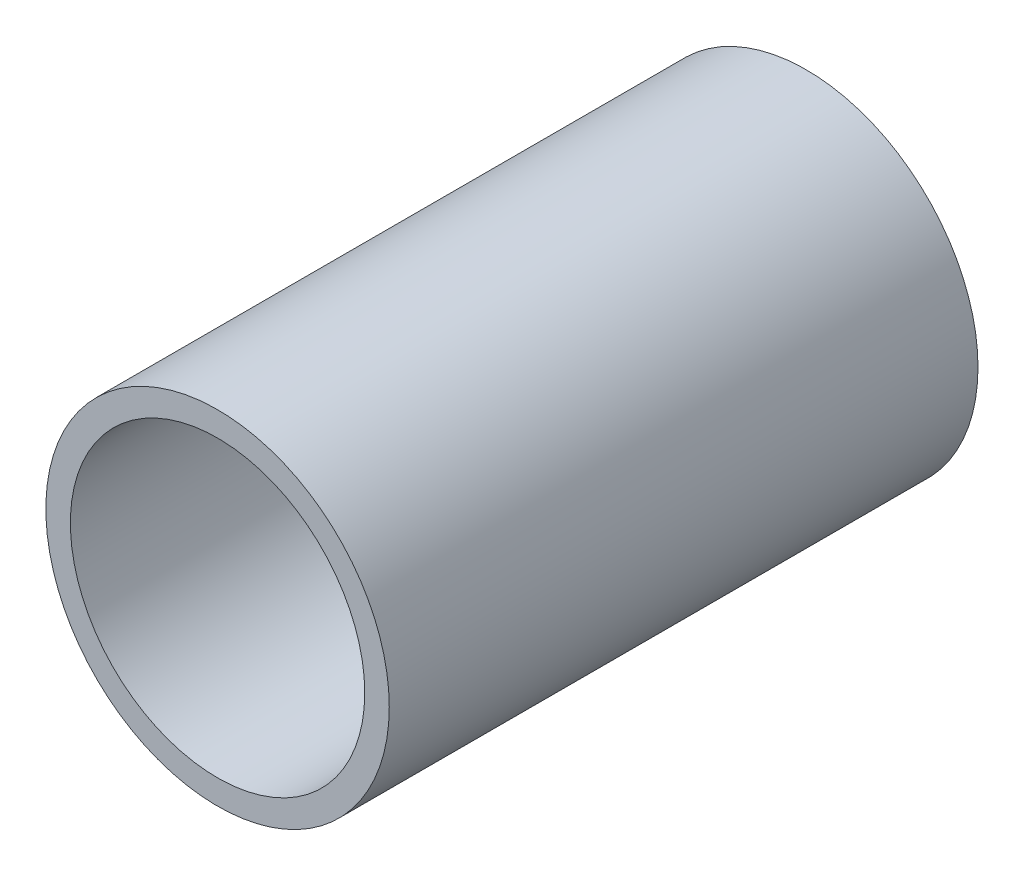
SolidWorks part; units mm, degrees
ref_plane "Alzado" through (0, 0, 0) normal (0, 0, 1) x (1, 0, 0)
ref_plane "Planta" through (0, 0, 0) normal (0, 1, 0) x (1, 0, 0)
ref_plane "Vista lateral" through (0, 0, 0) normal (1, 0, 0) x (0, 0, -1)
sketch "Croquis1" plane through (0, 0, 0) normal (0, 0, 1) x (1, 0, 0)
  circle A0 centre (0, 0) radius 35
  circle A1 centre (0, 0) radius 30
  dimension "D1" = 70
  dimension "D2" = 60
extrude "Saliente-Extruir1" add sketch "Croquis1" along normal blind 120
